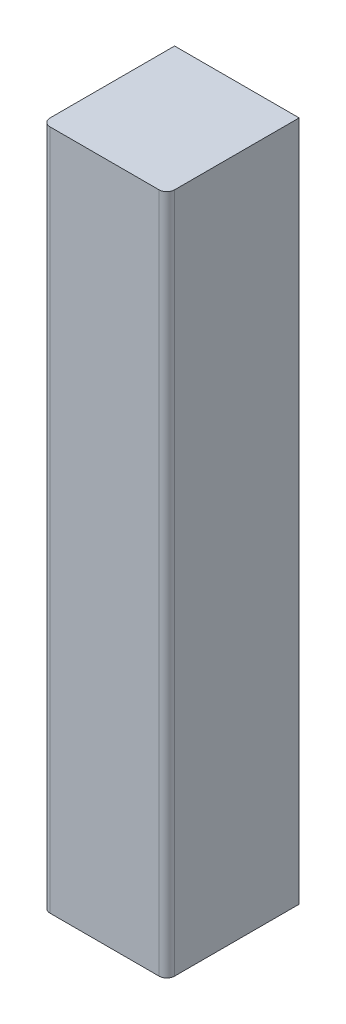
SolidWorks part; units mm, degrees
ref_plane "前视基准面" through (0, 0, 0) normal (0, 0, 1) x (1, 0, 0)
ref_plane "上视基准面" through (0, 0, 0) normal (0, 1, 0) x (1, 0, 0)
ref_plane "右视基准面" through (0, 0, 0) normal (1, 0, 0) x (0, 0, -1)
sketch "草图1" plane through (0, 0, 0) normal (0, 0, 1) x (1, 0, 0)
  line L0 (0, 48.626) -> (0, -83.7004) construction
  line L1 (-92.2698, 0) -> (95.8569, 0) construction
  line L2 (-8, 43.75) -> (8, 43.75)
  line L3 (-8, 43.75) -> (-8, -43.75)
  line L4 (-8, -43.75) -> (8, -43.75)
  line L5 (8, -43.75) -> (8, 43.75)
  dimension "D1" = 16
  dimension "D2" = 87.5
extrude "拉伸1" add sketch "草图1" along normal blind 0.1
sketch "草图2" plane through (0, 0, 0.1) normal (0, 0, 1) x (1, 0, 0)
  line L0 (0, 37.5456) -> (0, -35.199) construction
  line L1 (-34.3867, 0) -> (34.7477, 0) construction
  line L2 (-8, 43.75) -> (8, 43.75)
  line L3 (-8, 43.75) -> (-8, -43.75)
  line L4 (-8, -43.75) -> (8, -43.75)
  line L5 (8, -43.75) -> (8, 43.75)
  dimension "D1" = 16
  dimension "D2" = 87.5
extrude "拉伸2" add sketch "草图2" along normal blind 16.9
fillet "圆角1" radius 1 2 edges at (-8, 0, 17) (8, 0, 17)
